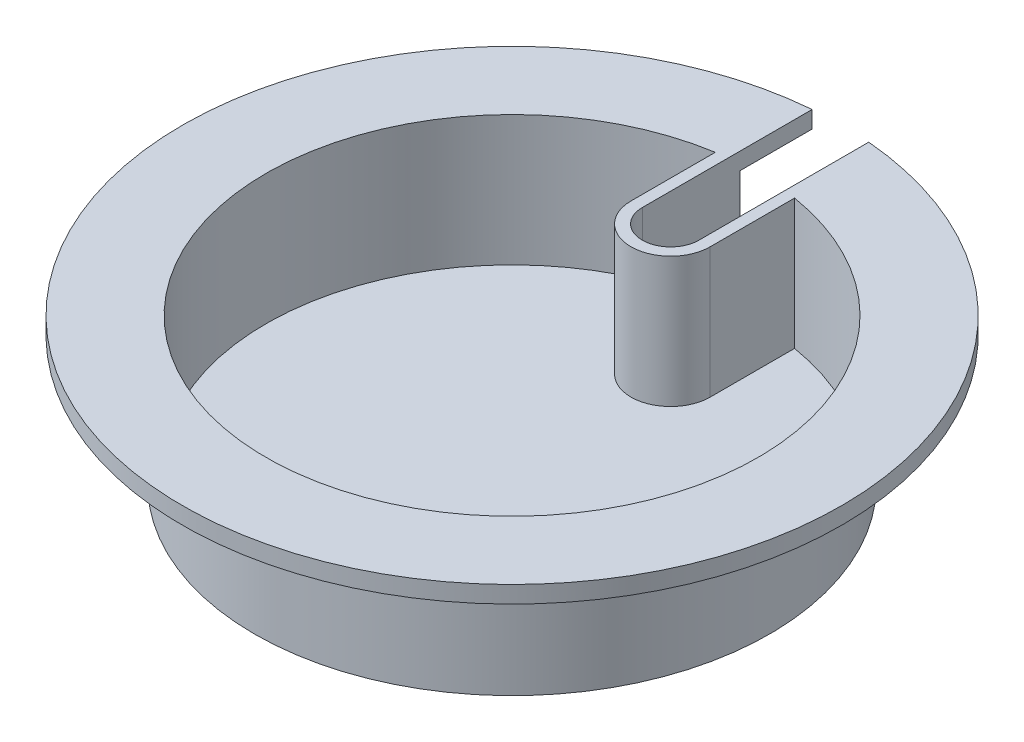
SolidWorks part; units mm, degrees
ref_plane "Front Plane" through (0, 0, 0) normal (0, 0, 1) x (1, 0, 0)
ref_plane "Top Plane" through (0, 0, 0) normal (0, 1, 0) x (1, 0, 0)
ref_plane "Right Plane" through (0, 0, 0) normal (1, 0, 0) x (0, 0, -1)
sketch "base" plane through (0, 0, 0) normal (0, 1, 0) x (1, 0, 0)
  line L0 (0, 0) -> (0, 22.75) construction
  line L1 (-2.5, 14) -> (-2.5, 22.6122)
  line L2 (2.5, 14) -> (2.5, 22.6122)
  arc A0 (-2.5, 22.6122) -> (2.5, 22.6122) centre (0, 0) ccw
  arc A2 (-2.5, 14) -> (2.5, 14) centre (0, 14) ccw
  point P3 (0, 14)
sketch "rim" plane through (0, 0, 0) normal (0, 1, 0) x (1, 0, 0)
  line L2 (-3.5, 21.4465) -> (-3.5, 14)
  line L3 (3.5, 14) -> (3.5, 21.4465)
  line L4 (2.5, 22.6122) -> (2.5, 14)
  line L5 (-2.5, 14) -> (-2.5, 22.6122)
  arc A0 (-2.5, 22.6122) -> (2.5, 22.6122) centre (0, 0) ccw
  arc A1 (-2.5, 22.6122) -> (2.5, 22.6122) centre (0, 0) ccw construction
  arc A2 (-3.5, 21.4465) -> (3.5, 21.4465) centre (0, 0) ccw
  arc A3 (-2.5, 14) -> (2.5, 14) centre (0, 14) ccw
  arc A4 (-2.5, 14) -> (2.5, 14) centre (0, 14) ccw construction
  arc A5 (-3.5, 14) -> (3.5, 14) centre (0, 14) ccw
sketch "lid" plane through (0, 0, 0) normal (0, 1, 0) x (1, 0, 0)
  line L0 (-3.5, 14) -> (-3.5, 21.4465)
  line L1 (2.5, 14) -> (2.5, 29)
  line L2 (-2.5, 14) -> (-2.5, 29)
  line L3 (3.5, 14) -> (3.5, 21.4465)
  arc A0 (-2.5, 14) -> (2.5, 14) centre (0, 14) ccw
  arc A1 (-2.5, 14) -> (2.5, 14) centre (0, 14) ccw construction
  arc A2 (-3.5, 14) -> (3.5, 14) centre (0, 14) ccw
  arc A4 (-3.5, 14) -> (3.5, 14) centre (0, 14) ccw construction
  arc A5 (-3.5, 21.4465) -> (3.5, 21.4465) centre (0, 0) ccw
  arc A6 (-3.5, 21.4465) -> (3.5, 21.4465) centre (0, 0) ccw construction
  arc A7 (-2.5, 29) -> (2.5, 29) centre (0, 0) ccw
extrude "Boss-Extrude11" add sketch "base" against normal blind 1.5 contours A0 L0 A2 L1 | L0 A0 L2 A2
extrude "Boss-Extrude12" add sketch "rim" along normal blind 10 contours A2 L3 A5 L2
extrude "Boss-Extrude15" add sketch "lid" along normal blind 1.5 from offset 10 contours L2 A7 L1 A0 A5 L0 A2 L3
